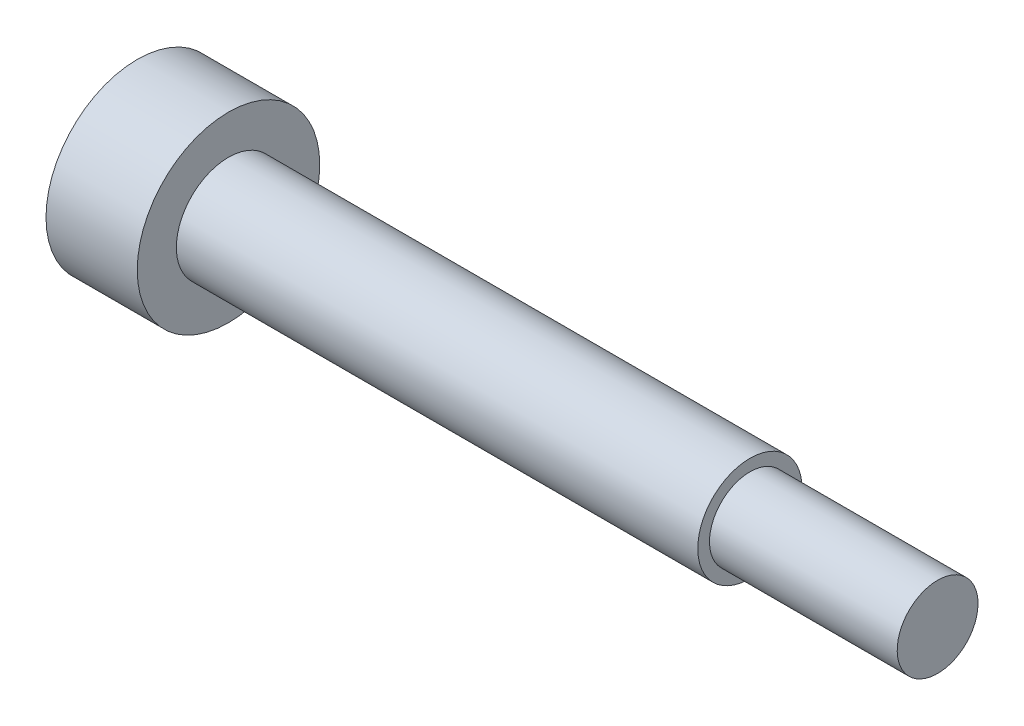
SolidWorks part; units mm, degrees
material "AISI 304"
ref_plane "前视基准面" through (0, 0, 0) normal (0, 0, 1) x (1, 0, 0)
ref_plane "上视基准面" through (0, 0, 0) normal (0, 1, 0) x (1, 0, 0)
ref_plane "右视基准面" through (0, 0, 0) normal (1, 0, 0) x (0, 0, -1)
other "Configuration Table"
sketch "草图1" plane through (0, 0, 0) normal (0, 0, 1) x (1, 0, 0)
  line L0 (0, 0) -> (0, 3.5)
  line L1 (0, 3.5) -> (3.5, 3.5)
  line L2 (3.5, 3.5) -> (3.5, 2)
  line L3 (3.5, 2) -> (23.5, 2)
  line L4 (23.5, 2) -> (23.5, 1.55)
  line L5 (23.5, 1.55) -> (30.7, 1.55)
  line L6 (30.7, 1.55) -> (30.7, 0)
  line L7 (30.7, 0) -> (0, 0)
  dimension "D1" = 3.5
  dimension "D2" = 20
  dimension "D3" = 7.2
  dimension "D4" = 1.55
  dimension "D5" = 3.5
  dimension "D6" = 2
revolve "旋转1" add sketch "草图1" angle 360 about L7
